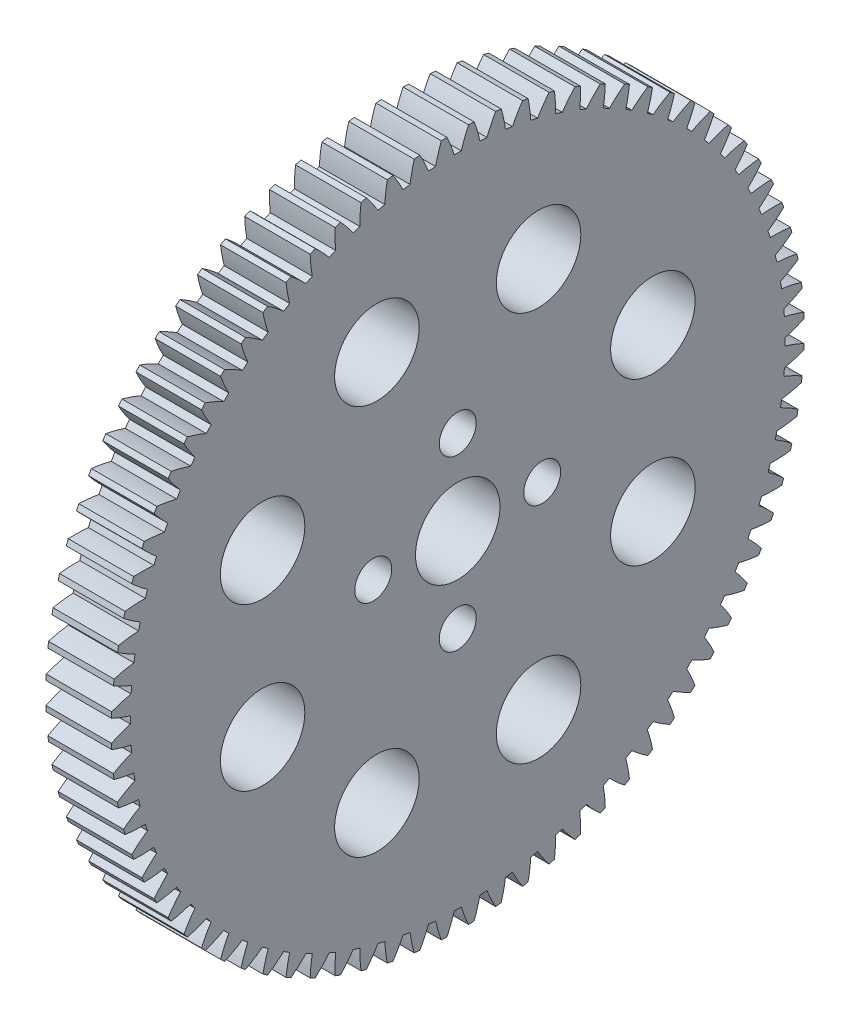
SolidWorks part; units mm, degrees
other "Defeature"
material "6061 Alloy"
ref_plane "Plane1" through (0, 0, 0) normal (0, 0, 1) x (1, 0, 0)
ref_plane "Plane2" through (0, 0, 0) normal (0, 1, 0) x (1, 0, 0)
ref_plane "Plane3" through (0, 0, 0) normal (1, 0, 0) x (0, 0, -1)
sketch "HoldingSke" plane through (0, 0, 0) normal (0, 1, 0) x (1, 0, 0)
  line L0 (0, 0) -> (0.2171, -1.231)
  line L1 (-15, 0) -> (100, 0) construction
  line L2 (0, 0) -> (-2.1039, 2.3779)
  line L3 (0, 0) -> (-11.863, 4.5341)
  line L4 (0, 0) -> (1.4996, 8.5048)
  line L5 (0, 0) -> (-46.8476, -17.4728)
  line L6 (0, 0) -> (-5.1396, -3.4677)
  line L7 (-2.1039, 2.3779) -> (8.6586, 51.2059)
  line L8 (-76.2, 54.61) -> (-74.8, 54.61)
  line L9 (-71.009, 38.7566) -> (-53.1078, 45.2721)
  line L10 (-76.2, 71.12) -> (104.1128, 71.12)
  line L11 (0, 0) -> (-6.2, 0)
  line L12 (-76.2, 101.6) -> (-76.17, 101.6)
  line L13 (24.9733, 27.94) -> (52.9518, 28.4284)
  line L14 (24.9733, 27.94) -> (24.9743, 27.94)
  line L15 (24.9733, 27.94) -> (100.4006, 29.5858)
  line L16 (-63.627, -0.8) -> (-12.827, -0.8)
  circle A0 centre (0, 0) radius 4
  circle A1 centre (0, 0) radius 30.999
  circle A2 centre (0, 0) radius 37.5
  circle A3 centre (0, 0) radius 4
  dimension "MHD" = 61.998
  dimension "Hub_dia" = 75
  dimension "Bore" = 8
  dimension "MBD" = 8
  dimension "Num_teeth" = 80
  dimension "Pitch_radius" = 180.3128
  dimension "Pitch" = 1.25
  dimension "Width" = 6.2
  dimension "Overall_len" = 50
  dimension "Show_teeth" = 80
  dimension "Thickness" = 6.2
  dimension "OAL" = 50.0001
  dimension "T_dim" = 1.4
  dimension "Ap" = 20
  dimension "H" = 19.05
  dimension "Backlash" = 0.03
  dimension "Addendum_fac" = 1
  dimension "Dedendum_fac" = 1.25
  dimension "Clearance_fac" = 0.25
  dimension "Dedendum_add" = 0.001
  dimension "Module" = 0.8
sketch "BasProSke" plane through (0, 0, 0) normal (0, 1, 0) x (1, 0, 0)
  line L0 (-10, 0) -> (60, 0) construction
  line L1 (0, 0) -> (0, 32.8)
  line L2 (0, 0) -> (6.2, 0)
  line L3 (6.2, 0) -> (6.2, 32.8)
  line L4 (6.2, 32.8) -> (0, 32.8)
  dimension "Diameter" = 65.6
  dimension "Thickness" = 6.2
revolve "Base-Revolve" add sketch "BasProSke" angle 360 about L0
sketch "TooCutSke" plane through (0, 0, 0) normal (1, 0, 0) x (0, 0, -1)
  line L1 (0, 0) -> (0, 107) construction
  line L2 (0, 0) -> (-0.6808, 31.9928) construction
  line L3 (0, 0) -> (-2.5122, 63.9403) construction
  line L4 (-0.6808, 31.9928) -> (-1.2561, 31.9702) construction
  arc A0 (0.3357, 30.9972) -> (-0.3357, 30.9972) centre (0, 0) ccw
  arc A1 (1.0352, 32.8091) -> (-1.0352, 32.8091) centre (0, 0) ccw
  circle A2 centre (0, 0) radius 32 construction
  circle A3 centre (0, 0) radius 30.0702 construction
  arc A4 (-0.3357, 30.9972) -> (-1.0352, 32.8091) centre (-12.5921, 27.3066) ccw
  arc A5 (1.0352, 32.8091) -> (0.3357, 30.9972) centre (12.5921, 27.3066) ccw
  dimension "Root_dia" = 61.998
  dimension "Overcut_dia" = 65.6508
  dimension "Pitch_dia" = 64
  dimension "Base_dia" = 60.1403
  dimension "Flank_rad" = 12.8
  dimension "Half_ang" = 2.25
  dimension "Half_CT" = 0.5758
extrude "ToothCut" cut sketch "TooCutSke" along normal through all
fillet "Breaks" [suppressed] radius 0.016
fillet "RootFillets" [suppressed] radius 0.201
pattern_circular "TeethCuts" count 80 every 4.5 about axis through (-10, 0, 0) along (1, 0, 0) of "ToothCut", "RootFillets", "Breaks"
sketch "HubNeaOneSke" plane through (0, 0, 0) normal (-1, 0, 0) x (0, 0, 1)
  circle A0 centre (0, 0) radius 30.999
  dimension "Diameter" = 61.998
extrude "HubNearOne" [suppressed] add sketch "HubNeaOneSke" along normal blind 43.8001
sketch "HubNeaBotSke" plane through (0, 0, 0) normal (-1, 0, 0) x (0, 0, 1)
  circle A0 centre (0, 0) radius 30.999
  dimension "Diameter" = 61.998
extrude "HubNearBoth" [suppressed] add sketch "HubNeaBotSke" along normal blind 21.9
ref_plane "FarPln" through (6.2, 0, 0) normal (1, 0, 0) x (0, 0, -1)
sketch "HubFarSke" plane through (6.2, 0, 0) normal (1, 0, 0) x (0, 0, -1)
  circle A0 centre (0, 0) radius 30.999
  dimension "Diameter" = 61.998
extrude "HubFar" [suppressed] add sketch "HubFarSke" along normal blind 21.9
sketch "BorSke" plane through (0, 0, 0) normal (1, 0, 0) x (0, 0, -1)
  circle A0 centre (0, 0) radius 4
  dimension "Diameter" = 8
extrude "Bore" cut sketch "BorSke" along normal mid plane 100.0001
sketch "KeySke" plane through (0, 0, 0) normal (1, 0, 0) x (0, 0, -1)
  line L0 (-1.5, 0) -> (-1.5, 5.4)
  line L1 (-1.5, 5.4) -> (1.5, 5.4)
  line L2 (1.5, 5.4) -> (1.5, 0)
  line L3 (0, 0) -> (0, 34) construction
  line L4 (-1.5, 0) -> (1.5, 0)
  dimension "Offset" = 5.4
  dimension "Width" = 3
extrude "Keyway" [suppressed] cut sketch "KeySke" along normal mid plane 100.0001
pattern_circular "Keyway2" [suppressed] count 2 every 90 about axis through (-10, 0, 0) along (1, 0, 0)
sketch "Sketch1" plane through (6.2, 0, 0) normal (1, 0, 0) x (0, 0, -1)
  line L0 (0, 0) -> (15.3073, 36.9552) construction
  line L1 (0, 0) -> (-13.1507, -31.7486) construction
  line L2 (0, 0) -> (31.0687, -12.8691) construction
  line L3 (0, 0) -> (-33.9622, 14.0676) construction
  line L4 (-18.4776, -7.6537) -> (18.4776, 7.6537) construction
  line L5 (-7.6537, 18.4776) -> (7.6537, -18.4776) construction
  line L6 (0, 0) -> (20, 0) construction
  circle A0 centre (-7.6537, 18.4776) radius 4
  circle A1 centre (7.6537, -18.4776) radius 4
  circle A2 centre (18.4776, 7.6537) radius 4
  circle A3 centre (-18.4776, -7.6537) radius 4
  circle A4 centre (7.6537, 18.4776) radius 4
  circle A5 centre (18.4776, -7.6537) radius 4
  circle A6 centre (-7.6537, -18.4776) radius 4
  circle A7 centre (-18.4776, 7.6537) radius 4
  circle A8 centre (0, 8) radius 1.75
  circle A9 centre (0, -8) radius 1.75
  circle A10 centre (8, 0) radius 1.75
  circle A11 centre (-8, 0) radius 1.75
  circle A12 centre (0, 0) radius 8 construction
  circle A13 centre (0, 0) radius 20 construction
  point P23 (0, 0)
  point P24 (0, 0)
  dimension "D1" = 8
  dimension "D2" = 16
  dimension "D3" = 45
  dimension "D4" = 22.5
  dimension "D5" = 40
  dimension "D17" = 3.5
extrude "Cut-Extrude1" cut sketch "Sketch1" against normal through all
equation "' \"Module@HoldingSke\" = 6.35"
equation "' \"Num_teeth@HoldingSke\" = 12"
equation "' \"Ap@HoldingSke\" =  20"
equation "' \"Width@HoldingSke\" = 0.5 * 25.4"
equation "' \"Hub_dia@HoldingSke\"= 1 * 25.4"
equation "' \"Overall_len@HoldingSke\" = 1.0 * 25.4"
equation "' \"Bore@HoldingSke\" = 0.75 * 25.4"
equation "' \"T_dim@HoldingSke\" = 0.1 * 25.4"
equation "' \"Width@KeySke\" = 0.25 * 25.4"
equation "' \"Show_teeth@HoldingSke\" = 13"
equation "' \"Backlash@HoldingSke\" = 0.009 * 25.4"
equation "' \"Addendum_fac@HoldingSke\" = 1.0"
equation "' \"Dedendum_fac@HoldingSke\" = 1.25"
equation "' \"Dedendum_add@HoldingSke\" = 0.00005 * 25.4"
equation "' \"Clearance_fac@HoldingSke\" = 0.25"
equation "\"Pitch@HoldingSke\" = 1 / \"Module@HoldingSke\""
equation "\"Overcut_dia@TooCutSke\" = (\"Num_teeth@HoldingSke\" + 2 * \"Addendum_fac@HoldingSke\") / \"Pitch@HoldingSke\" + 0.002 * 25.4"
equation "\"Pitch_dia@TooCutSke\" = \"Num_teeth@HoldingSke\" / \"Pitch@HoldingSke\""
equation "\"Base_dia@TooCutSke\" = \"Num_teeth@HoldingSke\" / \"Pitch@HoldingSke\" * cos((\"Ap@HoldingSke\"  * 3.14159265 / 180))"
equation "\"Root_dia@TooCutSke\" = (\"Num_teeth@HoldingSke\" + 2) / \"Pitch@HoldingSke\" - 2 * (\"Addendum_fac@HoldingSke\" + \"Dedendum_fac@HoldingSke\") / \"Pitch@HoldingSke\" - \"Dedendum_add@HoldingSke\" * 2"
equation "\"Half_ang@TooCutSke\" = 180 / \"Num_teeth@HoldingSke\""
equation "\"Half_CT@TooCutSke\" = \"Num_teeth@HoldingSke\" / \"Pitch@HoldingSke\" * sin((3.14159265 / 2 / \"Num_teeth@HoldingSke\")) / 2 - 7 * \"Backlash@HoldingSke\" / 4"
equation "\"Flank_rad@TooCutSke\" = \"Num_teeth@HoldingSke\" / \"Pitch@HoldingSke\" / 5"
equation "\"Radius@RootFillets\" = \"Clearance_fac@HoldingSke\" / \"Pitch@HoldingSke\" + \"Dedendum_add@HoldingSke\""
equation "\"Break_rad@Breaks\" = 0.02 / \"Pitch@HoldingSke\""
equation "\"Thickness@HoldingSke\" = \"Width@HoldingSke\""
equation "\"OAL@HoldingSke\" = \"Thickness@HoldingSke\""
equation "\"MHD@HoldingSke\" = (\"Num_teeth@HoldingSke\" + 2) / \"Pitch@HoldingSke\" - 2 * (\"Addendum_fac@HoldingSke\" + \"Dedendum_fac@HoldingSke\")  / \"Pitch@HoldingSke\" - \"Dedendum_add@HoldingSke\" * 2"
equation "\"MBD@HoldingSke\" = (\"Num_teeth@HoldingSke\" + 2) / \"Pitch@HoldingSke\" - 2 * (\"Addendum_fac@HoldingSke\" + \"Dedendum_fac@HoldingSke\")  / \"Pitch@HoldingSke\" - \"Dedendum_add@HoldingSke\" * 2 - 0.002 * 25.4"
equation "\"MHD@HoldingSke\" = ((sgn( \"MHD@HoldingSke\" - \"Hub_dia@HoldingSke\" )-1)*( \"MHD@HoldingSke\" - \"Hub_dia@HoldingSke\" ))/-2+ \"Hub_dia@HoldingSke\""
equation "\"MBD@HoldingSke\" = ((sgn( \"MBD@HoldingSke\" - \"Bore@HoldingSke\" )-1)*( \"MBD@HoldingSke\" - \"Bore@HoldingSke\" ))/-2+ \"Bore@HoldingSke\""
equation "\"OAL@HoldingSke\" = ((sgn( \"OAL@HoldingSke\" - \"Overall_len@HoldingSke\" )+1)*( \"OAL@HoldingSke\" - \"Overall_len@HoldingSke\" ))/2 + \"Overall_len@HoldingSke\" + 0.000002 * 25.4"
equation "\"Num_teeth@TeethCuts\" = int( \"Show_teeth@HoldingSke\" ) + 1"
equation "\"Num_teeth@TeethCuts\" = ((sgn( \"Num_teeth@TeethCuts\" - \"Num_teeth@HoldingSke\" )-1)*( \"Num_teeth@TeethCuts\" - \"Num_teeth@HoldingSke\" ))/-2+ \"Num_teeth@HoldingSke\""
equation "\"Num_teeth@TeethCuts\" = ((sgn( \"Num_teeth@TeethCuts\" - 2.0)+1)*( \"Num_teeth@TeethCuts\" - 2.0))/2 +2.0"
equation "\"Angle@TeethCuts\" = 360.0 / \"Num_teeth@HoldingSke\""
equation "\"Diameter@BasProSke\" = (\"Num_teeth@HoldingSke\" + 2 * \"Addendum_fac@HoldingSke\") / \"Pitch@HoldingSke\""
equation "\"Thickness@BasProSke\"  = \"Thickness@HoldingSke\""
equation "' \"Fillet_rad@BasProSke\" =  \"Thickness@HoldingSke\" * 0.05"
equation "\"MHD@HoldingSke\" = ((sgn( \"MHD@HoldingSke\" - \"Root_dia@TooCutSke\" )-1)*( \"MHD@HoldingSke\" - \"Root_dia@TooCutSke\" ))/-2+ \"Root_dia@TooCutSke\""
equation "\"Diameter@HubNeaOneSke\" = \"MHD@HoldingSke\""
equation "\"Length@HubNearOne\" = \"OAL@HoldingSke\" - \"Thickness@BasProSke\""
equation "\"Diameter@HubNeaBotSke\" = \"MHD@HoldingSke\""
equation "\"Length@HubNearBoth\" = ( \"OAL@HoldingSke\" - \"Thickness@BasProSke\" ) / 2.0"
equation "\"Thickness@FarPln\" = \"Thickness@BasProSke\""
equation "\"Diameter@HubFarSke\" = \"MHD@HoldingSke\""
equation "\"Length@HubFar\" = ( \"OAL@HoldingSke\" - \"Thickness@BasProSke\" ) / 2.0"
equation "\"Diameter@BorSke\" = \"MBD@HoldingSke\""
equation "\"D1@Bore\" = \"OAL@HoldingSke\" * 2.0"
equation "\"D1@Keyway\" = \"OAL@HoldingSke\" * 2.0"
equation "\"Offset@KeySke\" = \"T_dim@HoldingSke\" + \"MBD@HoldingSke\" / 2.0"
